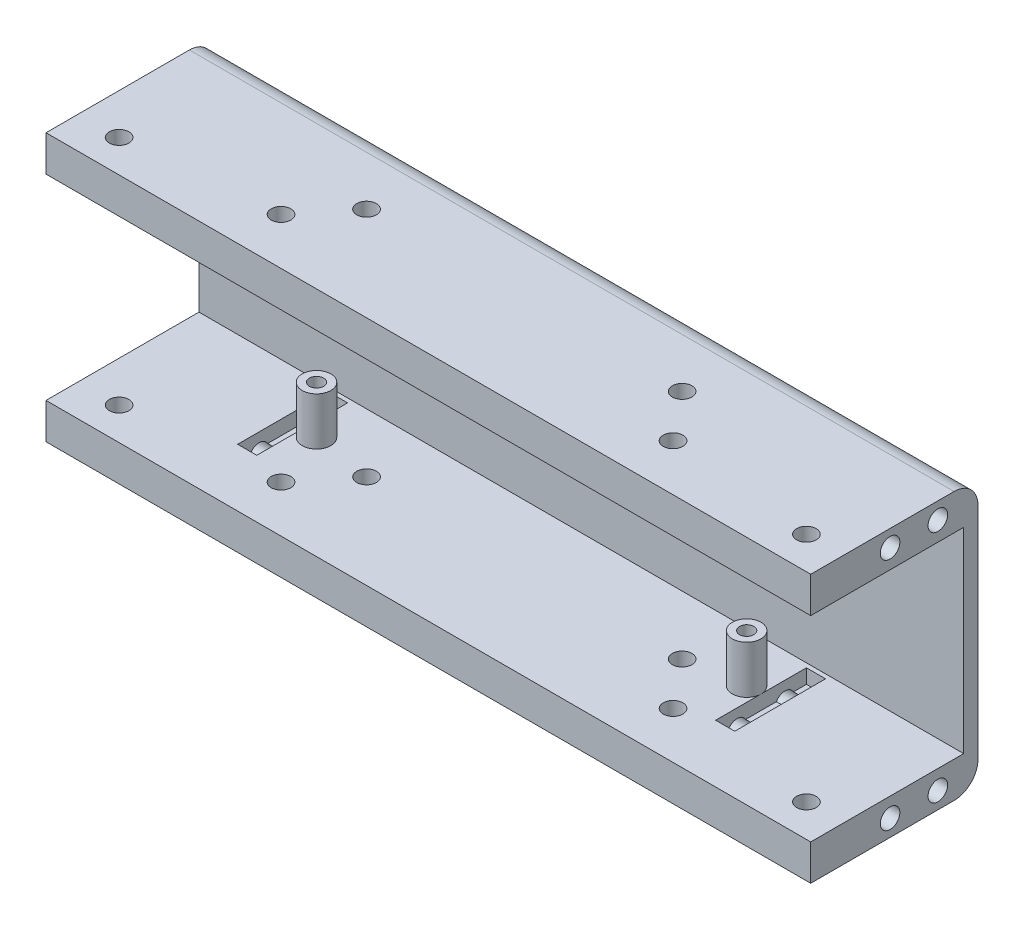
SolidWorks part; units mm, degrees
material "petg 20%"
ref_plane "Front Plane" through (0, 0, 0) normal (0, 0, 1) x (1, 0, 0)
ref_plane "Top Plane" through (0, 0, 0) normal (0, 1, 0) x (1, 0, 0)
ref_plane "Right Plane" through (0, 0, 0) normal (1, 0, 0) x (0, 0, -1)
sketch "Sketch1" plane through (0, 0, 0) normal (0, 0, 1) x (1, 0, 0)
  line L1 (-80, 28) -> (80, 28)
  line L2 (-80, 28) -> (-80, -28)
  line L3 (-80, -28) -> (80, -28)
  line L4 (80, 28) -> (80, -28)
  line L5 (-80, 28) -> (80, -28) construction
  line L6 (-80, -28) -> (80, 28) construction
  point P0 (0, 0)
  dimension "D1" = 160
  dimension "D2" = 56
extrude "Boss-Extrude1" add sketch "Sketch1" along normal blind 35
sketch "Sketch2" plane through (-80, 0, 0) normal (-1, 0, 0) x (0, 0, 1)
  line L0 (35, 28) -> (0, 28) construction
  line L1 (3, 20.5) -> (35, 20.5)
  line L2 (3, 20.5) -> (3, -20.5)
  line L3 (3, -20.5) -> (35, -20.5)
  line L4 (35, 20.5) -> (35, -20.5)
  line L5 (35, -28) -> (0, -28) construction
  line L6 (35, 28) -> (35, -28) construction
  line L7 (0, 28) -> (0, -28) construction
  dimension "D1" = 7.5
  dimension "D2" = 7.5
  dimension "D3" = 3
extrude "Cut-Extrude1" cut sketch "Sketch2" against normal through all
fillet "Fillet1" radius 5 2 edges at (0, -28, 0) (0, 28, 0)
sketch "Sketch6" plane through (0, 20.5, 0) normal (0, -1, 0) x (1, 0, 0)
  line L0 (-52, 22.9) -> (-52, 3.9)
  line L1 (-52, 22.9) -> (-48, 22.9)
  line L2 (-52, 3.9) -> (-48, 3.9)
  line L3 (-48, 22.9) -> (-48, 3.9)
  line L4 (80, 0) -> (-80, 0) construction
  line L5 (-80, 35) -> (-80, 3) construction
  dimension "D1" = 3.9
  dimension "D2" = 19
  dimension "D3" = 4
  dimension "D4" = 28
extrude "Cut-Extrude4" cut sketch "Sketch6" against normal blind 3
ref_plane "Plane1" through (0, 0, 0) normal (-1, 0, 0) x (0, 0, 1)
ref_plane "Plane2" through (0, 0, 0) normal (0, 1, 0) x (1, 0, 0)
mirror "Mirror3" about plane through (0, 0, 0) normal (-1, 0, 0) of "Cut-Extrude4"
mirror "Mirror4" about plane through (0, 0, 0) normal (0, 1, 0) of "Mirror3", "Cut-Extrude4"
sketch "Sketch8" plane through (-80, 0, 0) normal (-1, 0, 0) x (0, 0, 1)
  line L0 (35, -28) -> (5, -28) construction
  circle A1 centre (18.4, -24.5) radius 2.05
  circle A2 centre (8.4, -24.5) radius 2.05
  dimension "D1" = 4.1
  dimension "D2" = 4.1
  dimension "D3" = 3.5
  dimension "D4" = 10
extrude "Cut-Extrude6" cut sketch "Sketch8" against normal through all
mirror "Mirror5" about plane through (0, 0, 0) normal (0, 1, 0) of "Cut-Extrude6"
sketch "Sketch9" plane through (0, 28, 0) normal (0, 1, 0) x (1, 0, 0)
  circle A1 centre (41.4109, -25.2161) radius 2.05
  circle A2 centre (33.4109, -15.32) radius 2.05
  circle A3 centre (72.3044, -28.2033) radius 2.05
  circle A4 centre (-32.6109, -15.32) radius 2.05
  circle A5 centre (-40.6109, -25.2161) radius 2.05
  circle A7 centre (-71.5044, -28.2033) radius 2.05
extrude "Cut-Extrude7" cut sketch "Sketch9" against normal through all
sketch "Sketch10" plane through (0, -20.5, 0) normal (0, 1, 0) x (1, 0, 0)
  line L0 (0, 0) -> (0, -37.1263) construction
  line L1 (0, 19.25) -> (0, -19.25) construction
  line L2 (80, -35) -> (-80, -35) construction
  circle A0 centre (-45, -13.4) radius 1.5
  circle A1 centre (-45, -13.4) radius 3
  dimension "D1" = 45
  dimension "D2" = 21.6
  dimension "D3" = 3
  dimension "D4" = 6
extrude "Boss-Extrude3" add sketch "Sketch10" along normal blind 10
sketch "Sketch13" plane through (0, -10.5, 0) normal (0, 1, 0) x (1, 0, 0)
  line L0 (80, -35) -> (-80, -35) construction
  line L1 (0, 19.25) -> (0, -19.25) construction
  circle A0 centre (-45, -13.4) radius 1.5
  dimension "D1" = 21.6
  dimension "D2" = 45
  dimension "D3" = 3
extrude "Cut-Extrude9" cut sketch "Sketch13" against normal through all
mirror "Mirror6" about plane through (0, 0, 0) normal (-1, 0, 0) of "Boss-Extrude3", "Cut-Extrude9"
